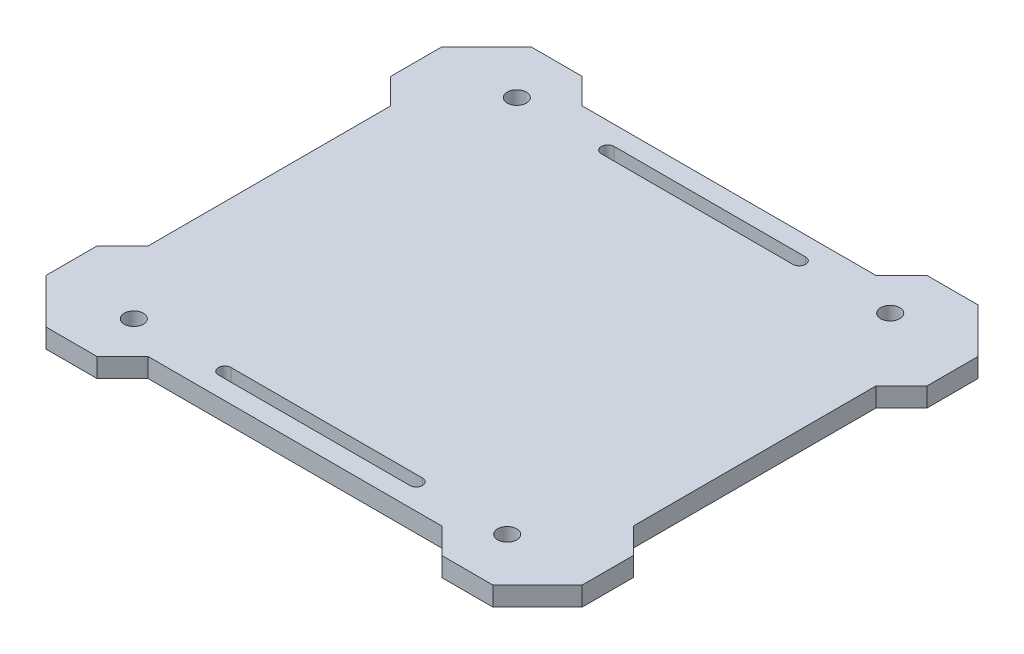
SolidWorks part; units mm, degrees
ref_plane "Front Plane" through (0, 0, 0) normal (0, 0, 1) x (1, 0, 0)
ref_plane "Top Plane" through (0, 0, 0) normal (0, 1, 0) x (1, 0, 0)
ref_plane "Right Plane" through (0, 0, 0) normal (1, 0, 0) x (0, 0, -1)
sketch "Sketch1" plane through (0, 0, 0) normal (0, 1, 0) x (1, 0, 0)
  line L18 (-23, 34) -> (23, 34)
  line L47 (-42, 31) -> (-35, 38)
  line L49 (-23, 34) -> (-27, 38)
  line L50 (-42, 31) -> (-42, 23)
  line L54 (-42, 23) -> (-38, 19)
  line L56 (-38, 19) -> (-38, -19)
  line L65 (-23, -34) -> (-27, -38)
  line L67 (-42, -31) -> (-35, -38)
  line L68 (-42, -31) -> (-42, -23)
  line L69 (-42, -23) -> (-38, -19)
  line L75 (-23, -34) -> (23, -34)
  line L77 (42, -31) -> (42, -23)
  line L78 (42, -23) -> (38, -19)
  line L79 (38, 19) -> (38, -19)
  line L80 (-27, 38) -> (-35, 38)
  line L81 (42, 23) -> (38, 19)
  line L85 (-27, -38) -> (-35, -38)
  line L86 (42, 31) -> (42, 23)
  line L87 (42, 31) -> (35, 38)
  line L88 (27, 38) -> (35, 38)
  line L89 (23, 34) -> (27, 38)
  line L92 (23, -34) -> (27, -38)
  line L93 (27, -38) -> (35, -38)
  line L94 (42, -31) -> (35, -38)
  point P0 (0, 0)
  point P1 (0, 0)
  point P45 (-38, 0)
  dimension "D1" = 8
extrude "Boss-Extrude1" add sketch "Sketch1" against normal blind 3
sketch "Sketch8" plane through (0, -3, 0) normal (0, -1, 0) x (1, 0, 0)
  line L1 (-27, -38) -> (-35, -38) construction
  circle A0 centre (-29.25, -30) radius 1.5
  circle A2 centre (29.25, -30) radius 1.5
  circle A3 centre (29.25, 30) radius 1.5
  circle A4 centre (-29.25, 30) radius 1.5
  dimension "D2" = 3
  dimension "D1" = 8
extrude "Cut-Extrude5" cut sketch "Sketch8" against normal through all
sketch "Sketch11" plane through (0, -3, 0) normal (0, -1, 0) x (1, 0, 0)
  line L10 (-15, -31) -> (15, -31)
  line L15 (15, -29) -> (-15, -29)
  line L21 (-15, 31) -> (15, 31)
  line L22 (15, 29) -> (-15, 29)
  line L29 (23, -34) -> (-23, -34) construction
  line L30 (-23, 34) -> (23, 34) construction
  arc A10 (-15, -29) -> (-15, -31) centre (-15, -30) ccw
  arc A11 (15, -29) -> (15, -31) centre (15, -30) cw
  arc A12 (15, 29) -> (15, 31) centre (15, 30) ccw
  arc A13 (-15, 29) -> (-15, 31) centre (-15, 30) cw
  dimension "D3" = 3
  dimension "D4" = 3
extrude "Cut-Extrude6" cut sketch "Sketch11" against normal blind 10
